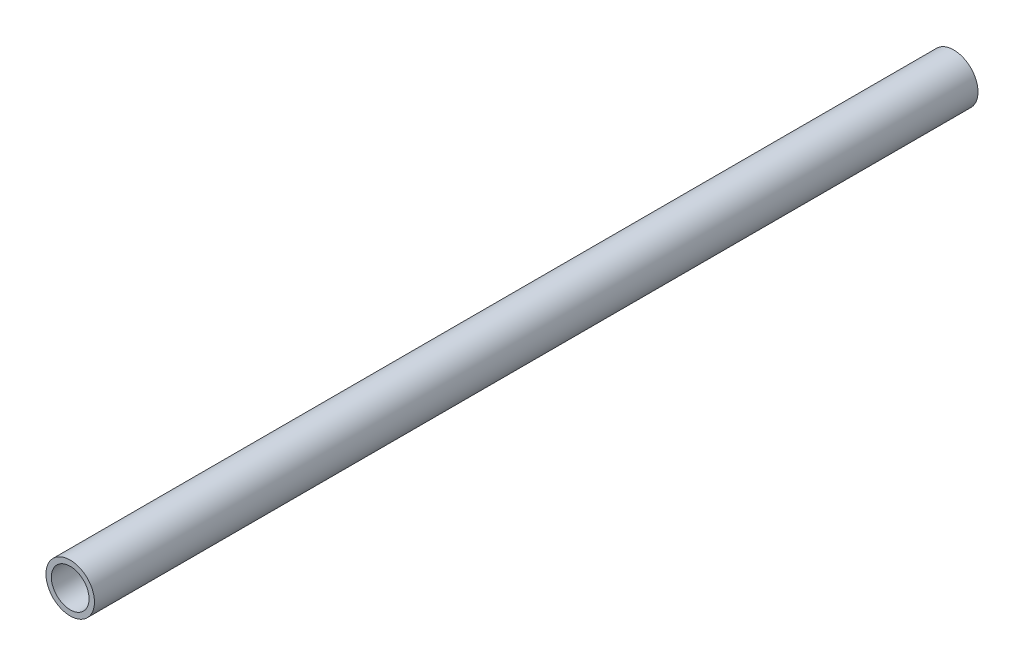
SolidWorks part; units mm, degrees
ref_plane "Front Plane" through (0, 0, 0) normal (0, 0, 1) x (1, 0, 0)
ref_plane "Top Plane" through (0, 0, 0) normal (0, 1, 0) x (1, 0, 0)
ref_plane "Right Plane" through (0, 0, 0) normal (1, 0, 0) x (0, 0, -1)
sketch "Sketch1" plane through (0, 0, 0) normal (0, 0, 1) x (1, 0, 0)
  line L0 (0, 0) -> (0, 7) construction
  line L1 (0, 0) -> (7, 0) construction
  circle A0 centre (0, 0) radius 9
  circle A1 centre (0, 0) radius 7
  point P5 (0, 0)
  dimension "D1" = 14
  dimension "D2" = 18
extrude "Boss-Extrude1" add sketch "Sketch1" along normal blind 327.978
sketch3d "3DSketch1"
  line L0 (0, 0, 327.978) -> (0, 0, 0) construction
  line L1 (0, 0, 327.978) -> (0, 0, 0) construction
  line L2 (0, 0, 327.978) -> (0, 0, 0) construction
  circle A0 centre (0, 0, 327.978) radius 9 construction
  point P7 (0, 0, 0)
  point P10 (0, 0, 336.978)
  point P11 (0, 0, 0)
  point P12 (0, 0, 327.978)
